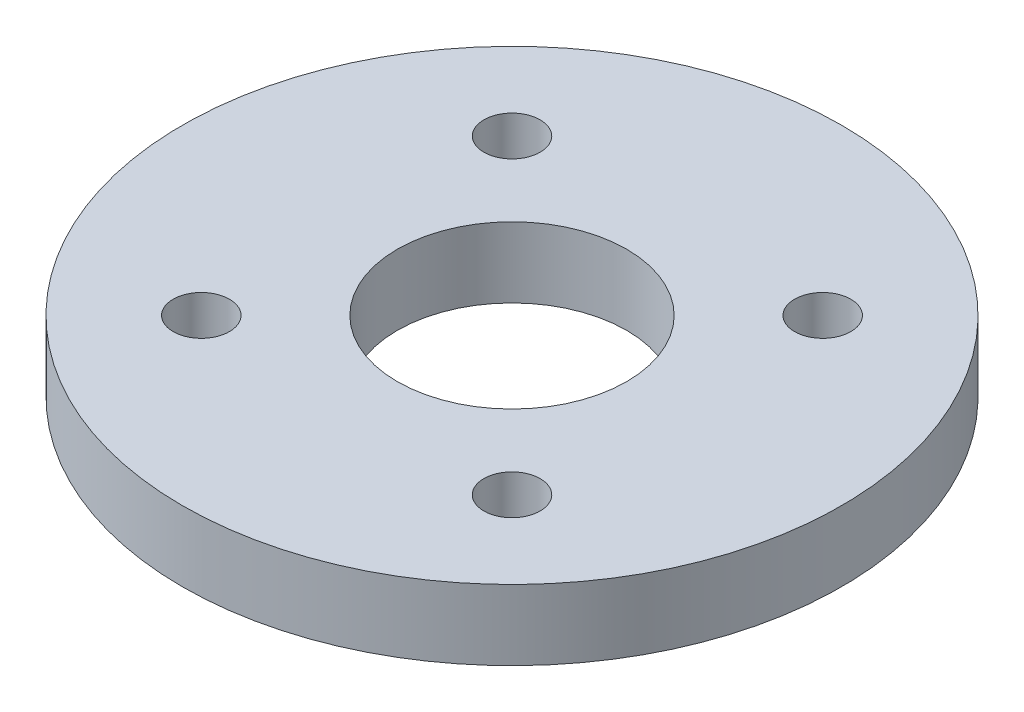
SolidWorks part; units mm, degrees
ref_plane "Front Plane" through (0, 0, 0) normal (0, 0, 1) x (1, 0, 0)
ref_plane "Top Plane" through (0, 0, 0) normal (0, 1, 0) x (1, 0, 0)
ref_plane "Right Plane" through (0, 0, 0) normal (1, 0, 0) x (0, 0, -1)
sketch "Sketch1" plane through (0, 0, 0) normal (0, 1, 0) x (1, 0, 0)
  line L1 (8.8388, 8.8388) -> (-8.8388, 8.8388) construction
  line L2 (-8.8388, 8.8388) -> (-8.8388, -8.8388) construction
  line L3 (-8.8388, -8.8388) -> (8.8388, -8.8388) construction
  line L4 (8.8388, -8.8388) -> (8.8388, 8.8388) construction
  circle A0 centre (0, 0) radius 18.75
  circle A1 centre (0, 0) radius 12.5 construction
  circle A2 centre (-8.8388, 8.8388) radius 1.6
  circle A3 centre (-8.8388, -8.8388) radius 1.6
  circle A4 centre (8.8388, -8.8388) radius 1.6
  circle A5 centre (8.8388, 8.8388) radius 1.6
  circle A6 centre (0, 0) radius 6.525
  dimension "D1" = 25
  dimension "D2" = 3.2
  dimension "D3" = 37.5
  dimension "D4" = 13.05
extrude "Boss-Extrude1" add sketch "Sketch1" along normal blind 4 contours A0 A5 L4 A4 L3 A3 L2 A2 L1 | A5 L1 A2 L2 A3 L3 A4 L4
